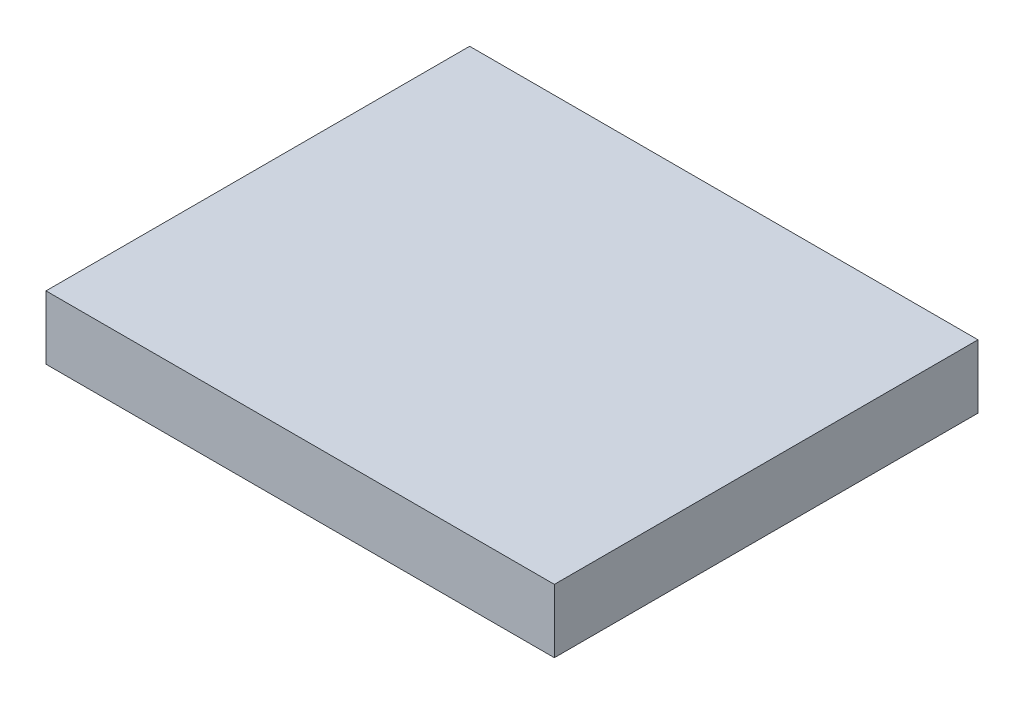
SolidWorks part; units mm, degrees
ref_plane "Front Plane" through (0, 0, 0) normal (0, 0, 1) x (1, 0, 0)
ref_plane "Top Plane" through (0, 0, 0) normal (0, 1, 0) x (1, 0, 0)
ref_plane "Right Plane" through (0, 0, 0) normal (1, 0, 0) x (0, 0, -1)
sketch "Sketch1" plane through (0, 0, 0) normal (0, 1, 0) x (1, 0, 0)
  line L1 (-609.6, 508) -> (609.6, 508)
  line L2 (-609.6, 508) -> (-609.6, -508)
  line L3 (-609.6, -508) -> (609.6, -508)
  line L4 (609.6, 508) -> (609.6, -508)
  line L5 (-609.6, 508) -> (609.6, -508) construction
  line L6 (-609.6, -508) -> (609.6, 508) construction
  point P0 (0, 0)
  dimension "D1" = 1219.2
  dimension "D2" = 1016
extrude "Boss-Extrude1" add sketch "Sketch1" along normal blind 152.4
